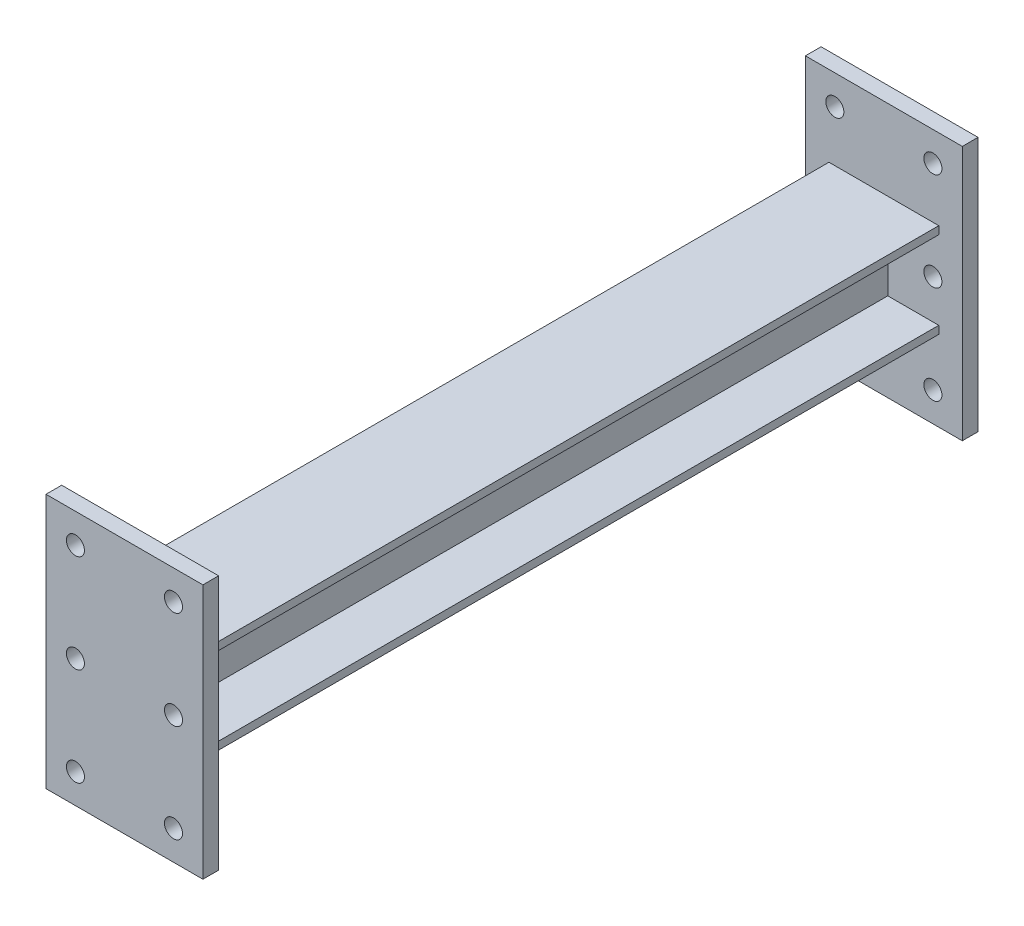
SolidWorks part; units mm, degrees
ref_plane "前视基准面" through (0, 0, 0) normal (0, 0, 1) x (1, 0, 0)
ref_plane "上视基准面" through (0, 0, 0) normal (0, 1, 0) x (1, 0, 0)
ref_plane "右视基准面" through (0, 0, 0) normal (1, 0, 0) x (0, 0, -1)
sketch "草图1" plane through (0, 0, 0) normal (0, 0, 1) x (1, 0, 0)
  line L0 (0, 120) -> (0, 110)
  line L1 (0, 0) -> (140, 0)
  line L2 (0, 110) -> (65, 110)
  line L3 (0, 120) -> (140, 120)
  line L4 (65, 110) -> (65, 10)
  line L5 (65, 10) -> (0, 10)
  line L6 (0, 10) -> (0, 0)
  line L7 (140, 120) -> (140, 110)
  line L8 (140, 110) -> (75, 110)
  line L9 (75, 110) -> (75, 10)
  line L10 (75, 10) -> (140, 10)
  line L11 (140, 10) -> (140, 0)
  line L12 (70, 120) -> (70, 0) construction
  dimension "D1" = 140
  dimension "D2" = 10
  dimension "D3" = 10
  dimension "D4" = 120
extrude "凸台-拉伸1" add sketch "草图1" along normal blind 948
sketch "草图2" plane through (0, 0, 948) normal (0, 0, 1) x (1, 0, 0)
  line L0 (70, -880) -> (70, 49120) construction
  line L1 (140, 120) -> (0, 120) construction
  line L2 (-869.2303, 60) -> (49130.7697, 60) construction
  line L3 (0, 0) -> (140, 0) construction
  line L5 (-30, 222.5) -> (170, 222.5)
  line L6 (-30, 222.5) -> (-30, -102.5)
  line L7 (-30, -102.5) -> (170, -102.5)
  line L8 (170, 222.5) -> (170, -102.5)
  point P5 (70, 120)
  dimension "D1" = 325
  dimension "D2" = 200
extrude "凸台-拉伸2" add sketch "草图2" along normal blind 20
sketch "草图3" plane through (0, 0, 0) normal (0, 0, -1) x (-1, 0, 0)
  line L1 (-170, 222.5) -> (30, 222.5)
  line L2 (-170, 222.5) -> (-170, -102.5)
  line L3 (-170, -102.5) -> (30, -102.5)
  line L4 (30, 222.5) -> (30, -102.5)
extrude "凸台-拉伸3" add sketch "草图3" along normal blind 20
sketch "草图4" plane through (0, 0, 968) normal (0, 0, 1) x (1, 0, 0)
  line L0 (70, -1102.5) -> (70, 48897.5) construction
  line L1 (-30, -102.5) -> (170, -102.5) construction
  line L2 (-830, 60) -> (49170, 60) construction
  line L3 (170, -102.5) -> (170, 222.5) construction
  circle A0 centre (7.5, 185) radius 11.5
  point P7 (70, -102.5)
  point P12 (170, 60)
  dimension "D1" = 23
  dimension "D2" = 62.5
  dimension "D3" = 125
extrude "切除-拉伸1" cut sketch "草图4" against normal through all
pattern_linear "阵列(线性)1" count 2 spacing 125 along (1, 0, 0) count 3 spacing 125 along (0, -1, 0) of "切除-拉伸1"
